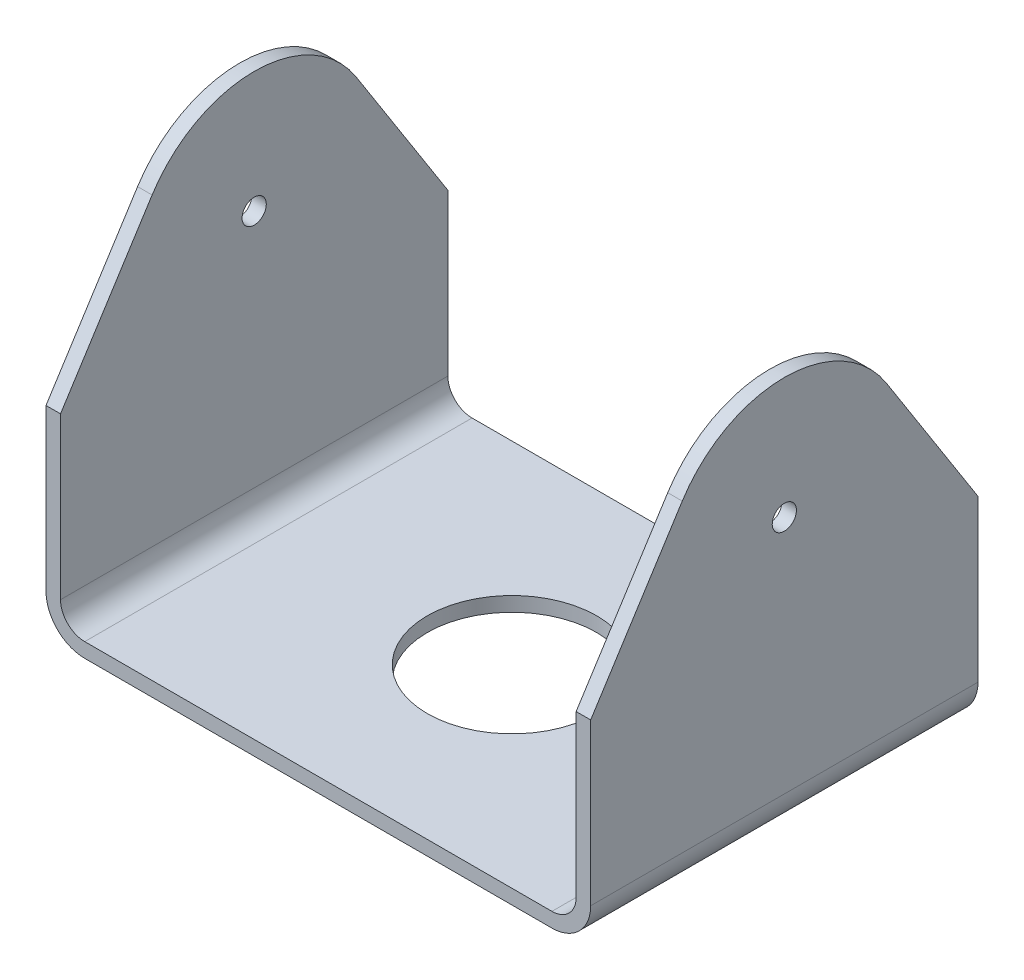
SolidWorks part; units mm, degrees
material "Alliage 1060"
ref_plane "Plan de face" through (0, 0, 0) normal (0, 0, 1) x (1, 0, 0)
ref_plane "Plan de dessus" through (0, 0, 0) normal (0, 1, 0) x (1, 0, 0)
ref_plane "Plan de droite" through (0, 0, 0) normal (1, 0, 0) x (0, 0, -1)
sketch "Esquisse1" plane through (0, 0, 0) normal (0, 0, 1) x (1, 0, 0)
  line L0 (-56.25, 82.5) -> (-56.25, 0)
  line L1 (-56.25, 0) -> (56.25, 0)
  line L2 (56.25, 0) -> (56.25, 82.5)
  dimension "D1" = 112.5
  dimension "D2" = 82.5
extrude "Extru.-Mince1" add sketch "Esquisse1" along normal mid plane 80 thin thin type one direction reverse wall 3
sketch "Esquisse2" plane through (0, 3, 0) normal (0, 1, 0) x (-1, 0, 0)
  circle A0 centre (0, 0) radius 17.5
  dimension "D1" = 35
extrude "Enlèv. mat.-Extru.1" cut sketch "Esquisse2" against normal up to next
sketch "Esquisse3" plane through (56.25, 0, 0) normal (1, 0, 0) x (0, 0, -1)
  line L1 (-40, 82.5) -> (40, 82.5) construction
  line L2 (-21.0848, 70.9325) -> (-40, 41.2416)
  line L3 (-40, 8) -> (-40, 82.5) construction
  line L4 (21.0848, 70.9325) -> (40, 41.2416)
  line L5 (40, 8) -> (40, 82.5) construction
  arc A0 (21.0848, 70.9325) -> (-21.0848, 70.9325) centre (0, 57.5) ccw
  dimension "D1" = 25
  dimension "D2" = 65
extrude "Enlèv. mat.-Extru.2" cut sketch "Esquisse3" against normal through all
sketch "Esquisse4" plane through (56.25, 0, 0) normal (1, 0, 0) x (0, 0, -1)
  circle A0 centre (0, 57.5) radius 2.5
  arc A1 (21.0848, 70.9325) -> (-21.0848, 70.9325) centre (0, 57.5) ccw construction
  dimension "D1" = 5
extrude "Enlèv. mat.-Extru.3" cut sketch "Esquisse4" against normal through all
